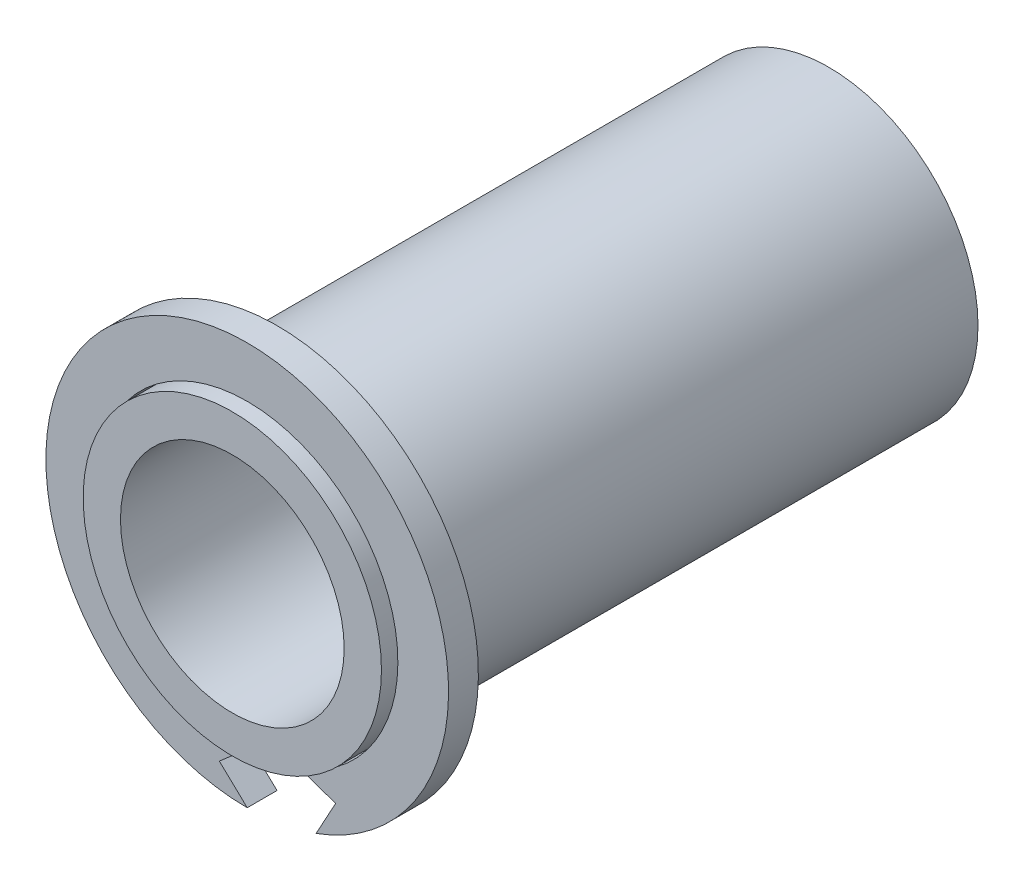
SolidWorks part; units mm, degrees
ref_plane "前视基准面" through (0, 0, 0) normal (0, 0, 1) x (1, 0, 0)
ref_plane "上视基准面" through (0, 0, 0) normal (0, 1, 0) x (1, 0, 0)
ref_plane "右视基准面" through (0, 0, 0) normal (1, 0, 0) x (0, 0, -1)
sketch "草图1" plane through (0, 0, 0) normal (0, 0, 1) x (1, 0, 0)
  circle A0 centre (0, 0) radius 4
  circle A1 centre (0, 0) radius 3
  dimension "D1" = 8
  dimension "D2" = 6
extrude "凸台-拉伸1" add sketch "草图1" along normal blind 16
sketch "草图2" plane through (0, 0, 16) normal (0, 0, 1) x (1, 0, 0)
  line L0 (0, 0) -> (0, -5.4)
  line L1 (0, 0) -> (1.8469, -5.0743) construction
  line L2 (0, -4.0405) -> (-0.7475, -4.6908)
  line L3 (-0.7475, -4.6908) -> (0, -5.4)
  line L4 (1.3681, -3.7588) -> (2.3698, -4.1166)
  line L5 (2.3698, -4.1166) -> (1.8469, -5.0743)
  circle A0 centre (0, 0) radius 5.4
  circle A1 centre (0, 0) radius 4.0405
  circle A2 centre (0, 0) radius 4.75
  circle A3 centre (0, 0) radius 4 construction
  dimension "D1" = 10.8
  dimension "D3" = 9.5
  dimension "D2" = 20
extrude "凸台-拉伸2" add sketch "草图2" against normal blind 0.8 from offset 0.4 separate body contours A2 L5 A0 L3 | L4 A2 L2 A1 offset against normal yes
